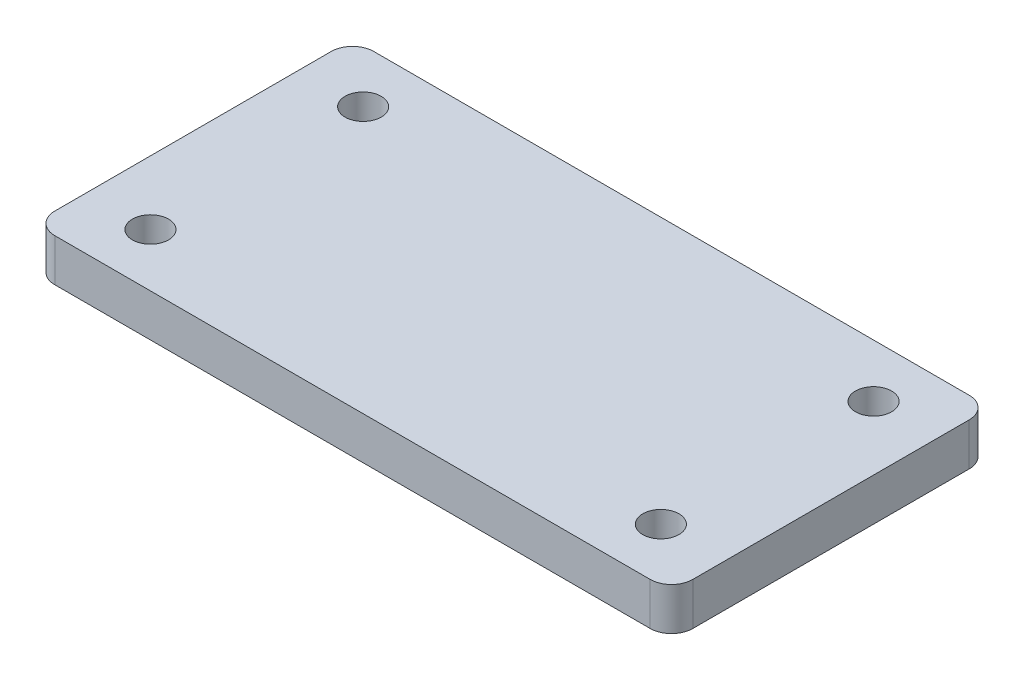
SolidWorks part; units mm, degrees
ref_plane "Front Plane" through (0, 0, 0) normal (0, 0, 1) x (1, 0, 0)
ref_plane "Top Plane" through (0, 0, 0) normal (0, 1, 0) x (1, 0, 0)
ref_plane "Right Plane" through (0, 0, 0) normal (1, 0, 0) x (0, 0, -1)
sketch "Sketch1" plane through (0, 0, 0) normal (0, 1, 0) x (1, 0, 0)
  line L1 (-150, -75) -> (150, -75)
  line L2 (-150, -75) -> (-150, 75)
  line L3 (-150, 75) -> (150, 75)
  line L4 (150, -75) -> (150, 75)
  line L5 (-150, -75) -> (150, 75) construction
  line L6 (-150, 75) -> (150, -75) construction
  point P0 (0, 0)
extrude "Boss-Extrude1" add sketch "Sketch1" along normal blind 20
fillet "Fillet1" radius 10 4 edges at (150, 10, -75) (150, 10, 75) (-150, 10, 75) (-150, 10, -75)
sketch "Sketch2" plane through (0, 20, 0) normal (0, 1, 0) x (1, 0, 0)
  line L1 (-120, -50) -> (120, -50)
  line L2 (-120, -50) -> (-120, 50)
  line L3 (-120, 50) -> (120, 50)
  line L4 (120, -50) -> (120, 50)
  line L5 (-120, -50) -> (120, 50) construction
  line L6 (-120, 50) -> (120, -50) construction
  point P0 (0, 0)
  dimension "D1" = 240
  dimension "D2" = 100
hole_wizard "Ø17.0 (17) Diameter Hole1" positions "3DSketch1" profile "Sketch3" hole size "Ø17.0" standard "ISO" end condition through all
sketch3d "3DSketch1"
  point P0 (-120, 20, -50)
  point P3 (-120, 20, 50)
  point P6 (120, 20, -50)
  point P9 (120, 20, 50)
sketch "Sketch3" plane through (-120, 20, -50) normal (1, 0, 0) x (0, 0, 1)
  line L0 (0, 0) -> (0, 20)
  line L1 (0, 20) -> (8.5, 20)
  line L2 (8.5, 20) -> (8.5, 0)
  line L5 (8.5, 0) -> (0, 0)
  line L11 (0, -6.35) -> (0, 107.95) construction
  dimension "Thru Hole Dia." = 17
  dimension "Thru Hole Depth" = 20
hole_wizard "M16 Tapped Hole1" [suppressed] positions "3DSketch2" profile "Sketch4" tap size "M16" standard "ISO"
sketch3d "3DSketch2"
  point P0 (120, 20, 50)
  point P3 (120, 20, -50)
  point P6 (-120, 20, 50)
  point P9 (-120, 20, -50)
sketch "Sketch4" plane through (120, 20, 50) normal (1, 0, 0) x (0, 0, 1)
  line L0 (0, 0) -> (0, 20)
  line L1 (0, 20) -> (7, 20)
  line L2 (7, 20) -> (7, 0)
  line L5 (7, 0) -> (0, 0)
  line L11 (0, -6.35) -> (0, 107.95) construction
  dimension "Thru Tap Drill Dia." = 14
  dimension "Thru Tap Drill Depth" = 20
cosmetic thread "Hole Thread1" [suppressed] parameters "D2"=16
cosmetic thread "Hole Thread2" [suppressed] parameters "D2"=16
cosmetic thread "Hole Thread3" [suppressed] parameters "D2"=16
cosmetic thread "Hole Thread4" [suppressed] parameters "D2"=16
